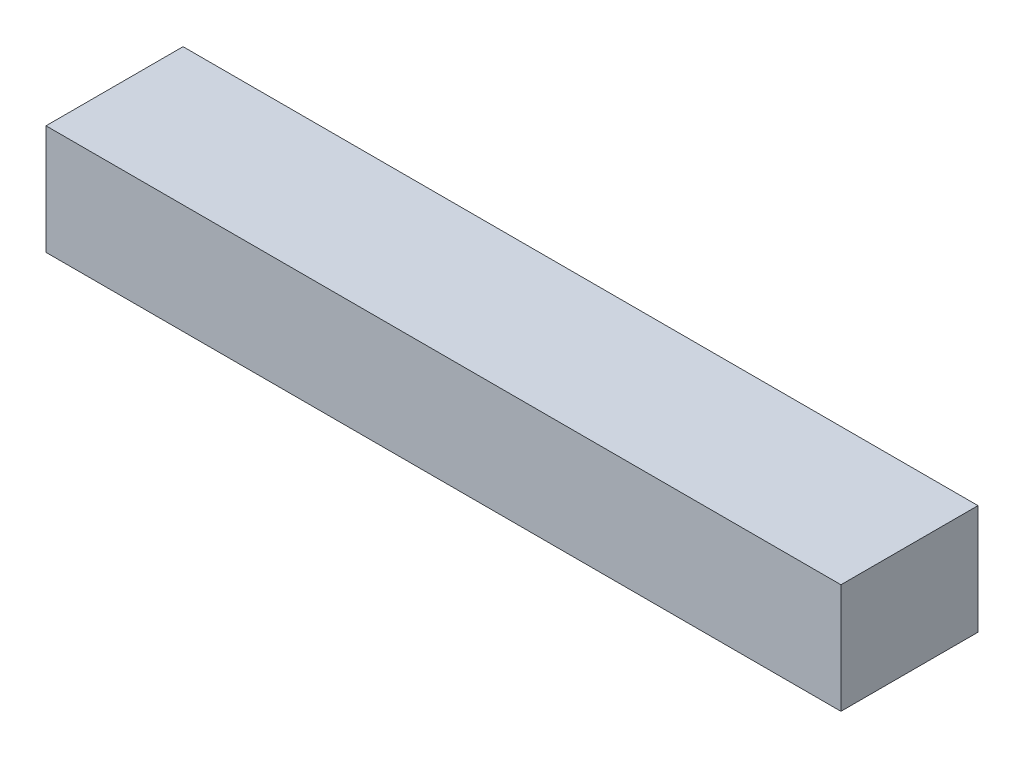
SolidWorks part; units mm, degrees
ref_plane "Front Plane" through (0, 0, 0) normal (0, 0, 1) x (1, 0, 0)
ref_plane "Top Plane" through (0, 0, 0) normal (0, 1, 0) x (1, 0, 0)
ref_plane "Right Plane" through (0, 0, 0) normal (1, 0, 0) x (0, 0, -1)
sketch "Sketch1" plane through (0, 0, 0) normal (0, 1, 0) x (1, 0, 0)
  line L0 (0, 0) -> (0, 12.7)
  line L1 (0, 12.7) -> (73.66, 12.7)
  line L2 (73.66, 12.7) -> (73.66, 0)
  line L3 (73.66, 0) -> (0, 0)
  dimension "D1" = 12.7
  dimension "D2" = 73.66
extrude "Boss-Extrude1" add sketch "Sketch1" along normal blind 10.16
